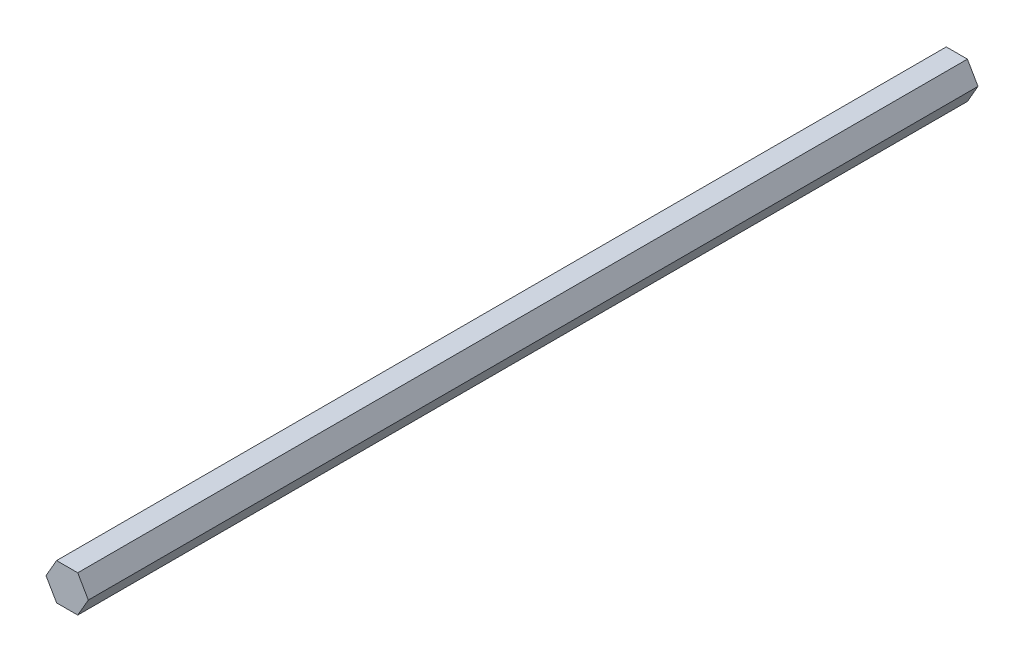
SolidWorks part; units mm, degrees
other "Axis1"
material "Alloy Steel"
ref_plane "Front" through (0, 0, 0) normal (0, 0, 1) x (1, 0, 0)
ref_plane "Top" through (0, 0, 0) normal (0, 1, 0) x (1, 0, 0)
ref_plane "Right" through (0, 0, 0) normal (1, 0, 0) x (0, 0, -1)
sketch "AxisSke" plane through (0, 0, 0) normal (0, 0, 1) x (1, 0, 0)
  line L1 (0.9988, 0) -> (0.4994, 0.865)
  line L2 (0.4994, 0.865) -> (-0.4994, 0.865)
  line L3 (-0.4994, 0.865) -> (-0.9988, 0)
  line L4 (-0.9988, 0) -> (-0.4994, -0.865)
  line L5 (-0.4994, -0.865) -> (0.4994, -0.865)
  line L6 (0.4994, -0.865) -> (0.9988, 0)
  circle A0 centre (0, 0) radius 0.865 construction
  dimension "D1" = 1.73
extrude "Axis" add sketch "AxisSke" along normal blind 42
